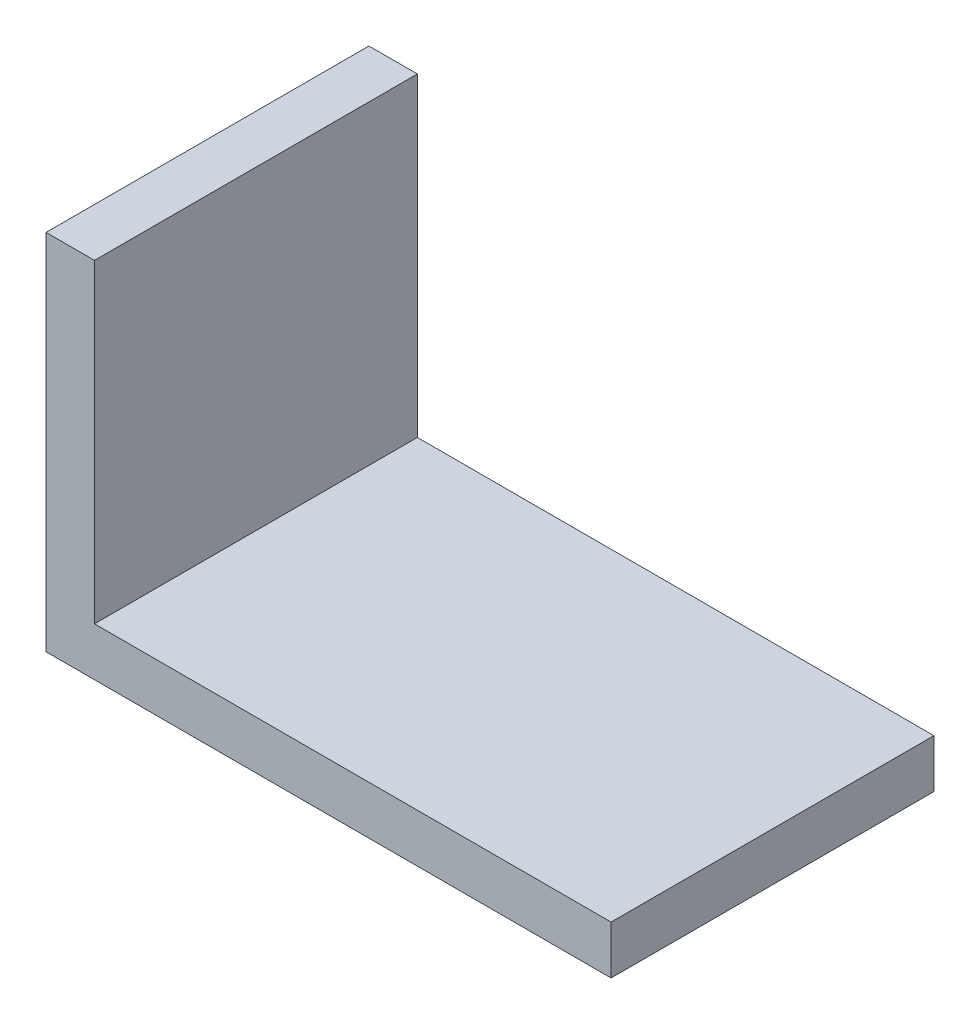
SolidWorks part; units mm, degrees
ref_plane "前视基准面" through (0, 0, 0) normal (0, 0, 1) x (1, 0, 0)
ref_plane "上视基准面" through (0, 0, 0) normal (0, 1, 0) x (1, 0, 0)
ref_plane "右视基准面" through (0, 0, 0) normal (1, 0, 0) x (0, 0, -1)
other "Configuration Table"
sketch "草图8" plane through (0, 0, 0) normal (0, 0, 1) x (1, 0, 0)
  line L0 (0, 0) -> (140, 0)
  line L1 (140, 0) -> (140, 12)
  line L2 (140, 12) -> (12, 12)
  line L3 (12, 12) -> (12, 90)
  line L4 (12, 90) -> (0, 90)
  line L5 (0, 90) -> (0, 0)
extrude "凸台-拉伸1" add sketch "草图8" along normal mid plane 80
